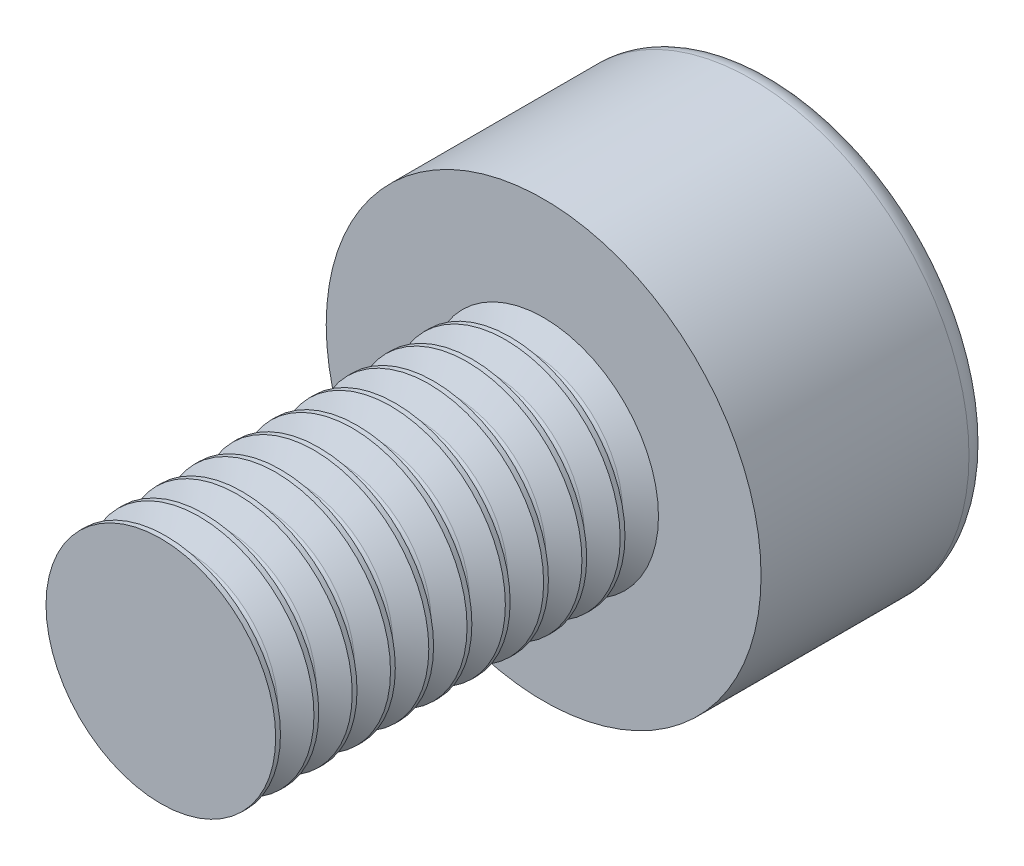
SolidWorks part; units mm, degrees
ref_plane "Front Plane" through (0, 0, 0) normal (0, 0, 1) x (1, 0, 0)
ref_plane "Top Plane" through (0, 0, 0) normal (0, 1, 0) x (1, 0, 0)
ref_plane "Right Plane" through (0, 0, 0) normal (1, 0, 0) x (0, 0, -1)
ref_plane "Plane1" through (0, 0, 0) normal (0, -1, 0) x (1, 0, 0)
sketch "Sketch1" plane through (0, 0, 0) normal (0, -1, 0) x (1, 0, 0)
  line L2 (0, -3) -> (2.84, -3)
  line L3 (2.84, -3) -> (2.84, 0)
  line L4 (2.84, 0) -> (1.5, 0)
  line L5 (1.5, 0) -> (1.2023, 0.1719)
  line L6 (1.2023, 0.2656) -> (1.5, 0.4375)
  line L7 (1.5, 0.4375) -> (1.5, 0.5)
  line L8 (1.5, 0.5) -> (1.2023, 0.6719)
  line L9 (1.2023, 0.7656) -> (1.5, 0.9375)
  line L10 (1.5, 0.9375) -> (1.5, 1)
  line L11 (1.5, 1) -> (1.2023, 1.1719)
  line L12 (1.2023, 1.2656) -> (1.5, 1.4375)
  line L13 (1.5, 1.4375) -> (1.5, 1.5)
  line L14 (1.5, 1.5) -> (1.2023, 1.6719)
  line L15 (1.2023, 1.7656) -> (1.5, 1.9375)
  line L16 (1.5, 1.9375) -> (1.5, 2)
  line L17 (1.5, 2) -> (1.2023, 2.1719)
  line L18 (1.2023, 2.2656) -> (1.5, 2.4375)
  line L19 (1.5, 2.4375) -> (1.5, 2.5)
  line L20 (1.5, 2.5) -> (1.2023, 2.6719)
  line L21 (1.2023, 2.7656) -> (1.5, 2.9375)
  line L22 (1.5, 2.9375) -> (1.5, 3)
  line L23 (1.5, 3) -> (1.2023, 3.1719)
  line L24 (1.2023, 3.2656) -> (1.5, 3.4375)
  line L25 (1.5, 3.4375) -> (1.5, 3.5)
  line L26 (1.5, 3.5) -> (1.2023, 3.6719)
  line L27 (1.2023, 3.7656) -> (1.5, 3.9375)
  line L28 (1.5, 3.9375) -> (1.5, 4)
  line L29 (1.5, 4) -> (1.2023, 4.1719)
  line L30 (1.2023, 4.2656) -> (1.5, 4.4375)
  line L31 (1.5, 4.4375) -> (1.5, 4.5)
  line L32 (1.5, 4.5) -> (1.2023, 4.6719)
  line L33 (1.2023, 4.7656) -> (1.5, 4.9375)
  line L34 (1.5, 4.9375) -> (1.5, 5)
  line L95 (0, -3) -> (0, 5)
  line L96 (0, 5) -> (1.5, 5)
  spline S0 degree 3 poles (1.1752, 0.2188) (1.1752, 0.2007) (1.1867, 0.1809) (1.2023, 0.1719) knots 0 0 0 0 1 1 1 1
  spline S1 degree 3 poles (1.2023, 0.2656) (1.1867, 0.2566) (1.1752, 0.2368) (1.1752, 0.2188) knots 0 0 0 0 1 1 1 1
  spline S2 degree 3 poles (1.2023, 0.6719) (1.1867, 0.6809) (1.1752, 0.7007) (1.1752, 0.7188) knots 0 0 0 0 1 1 1 1
  spline S3 degree 3 poles (1.1752, 0.7188) (1.1752, 0.7368) (1.1867, 0.7566) (1.2023, 0.7656) knots 0 0 0 0 1 1 1 1
  spline S4 degree 3 poles (1.2023, 1.1719) (1.1867, 1.1809) (1.1752, 1.2007) (1.1752, 1.2188) knots 0 0 0 0 1 1 1 1
  spline S5 degree 3 poles (1.1752, 1.2188) (1.1752, 1.2368) (1.1867, 1.2566) (1.2023, 1.2656) knots 0 0 0 0 1 1 1 1
  spline S6 degree 3 poles (1.2023, 1.6719) (1.1867, 1.6809) (1.1752, 1.7007) (1.1752, 1.7188) knots 0 0 0 0 1 1 1 1
  spline S7 degree 3 poles (1.1752, 1.7188) (1.1752, 1.7368) (1.1867, 1.7566) (1.2023, 1.7656) knots 0 0 0 0 1 1 1 1
  spline S8 degree 3 poles (1.2023, 2.1719) (1.1867, 2.1809) (1.1752, 2.2007) (1.1752, 2.2188) knots 0 0 0 0 1 1 1 1
  spline S9 degree 3 poles (1.1752, 2.2188) (1.1752, 2.2368) (1.1867, 2.2566) (1.2023, 2.2656) knots 0 0 0 0 1 1 1 1
  spline S10 degree 3 poles (1.2023, 2.6719) (1.1867, 2.6809) (1.1752, 2.7007) (1.1752, 2.7188) knots 0 0 0 0 1 1 1 1
  spline S11 degree 3 poles (1.1752, 2.7188) (1.1752, 2.7368) (1.1867, 2.7566) (1.2023, 2.7656) knots 0 0 0 0 1 1 1 1
  spline S12 degree 3 poles (1.2023, 3.1719) (1.1867, 3.1809) (1.1752, 3.2007) (1.1752, 3.2188) knots 0 0 0 0 1 1 1 1
  spline S13 degree 3 poles (1.1752, 3.2188) (1.1752, 3.2368) (1.1867, 3.2566) (1.2023, 3.2656) knots 0 0 0 0 1 1 1 1
  spline S14 degree 3 poles (1.2023, 3.6719) (1.1867, 3.6809) (1.1752, 3.7007) (1.1752, 3.7188) knots 0 0 0 0 1 1 1 1
  spline S15 degree 3 poles (1.1752, 3.7188) (1.1752, 3.7368) (1.1867, 3.7566) (1.2023, 3.7656) knots 0 0 0 0 1 1 1 1
  spline S16 degree 3 poles (1.2023, 4.1719) (1.1867, 4.1809) (1.1752, 4.2007) (1.1752, 4.2188) knots 0 0 0 0 1 1 1 1
  spline S17 degree 3 poles (1.1752, 4.2188) (1.1752, 4.2368) (1.1867, 4.2566) (1.2023, 4.2656) knots 0 0 0 0 1 1 1 1
  spline S18 degree 3 poles (1.2023, 4.6719) (1.1867, 4.6809) (1.1752, 4.7007) (1.1752, 4.7188) knots 0 0 0 0 1 1 1 1
  spline S19 degree 3 poles (1.1752, 4.7188) (1.1752, 4.7368) (1.1867, 4.7566) (1.2023, 4.7656) knots 0 0 0 0 1 1 1 1
  dimension "D1" = 8
  dimension "D2" = 3
  dimension "D3" = 2.84
  dimension "D4" = 1.34
  dimension "D5" = 3
  dimension "D6" = 2.84
  dimension "D7" = 1.5
revolve "Revolve1" add sketch "Sketch1" angle 360 about L95
sketch "Sketch2" plane through (0, 0, -3) normal (0, 0, -1) x (-1, 0, 0)
  line L0 (-1.4434, 0) -> (-0.7217, -1.25)
  line L1 (-0.7217, -1.25) -> (0.7217, -1.25)
  line L2 (0.7217, -1.25) -> (1.4434, 0)
  line L3 (1.4434, 0) -> (0.7217, 1.25)
  line L4 (0.7217, 1.25) -> (-0.7217, 1.25)
  line L5 (-0.7217, 1.25) -> (-1.4434, 0)
extrude "Cut-Extrude1" cut sketch "Sketch2" against normal blind 1.5
fillet "Fillet1" radius 0.284 1 edges at (2.84, 0, -3)
